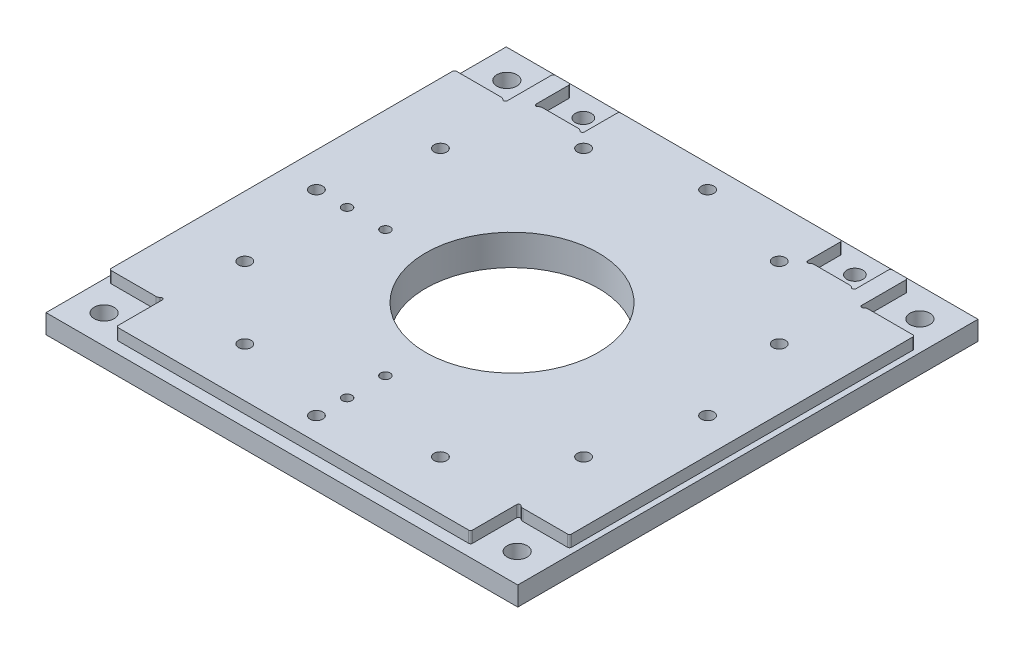
SolidWorks part; units mm, degrees
ref_plane "Front Plane" through (0, 0, 0) normal (0, 0, 1) x (1, 0, 0)
ref_plane "Top Plane" through (0, 0, 0) normal (0, 1, 0) x (1, 0, 0)
ref_plane "Right Plane" through (0, 0, 0) normal (1, 0, 0) x (0, 0, -1)
other "Configuration Table"
sketch "草图1" plane through (0, 0, 0) normal (0, 1, 0) x (1, 0, 0)
  line L1 (-60, 60) -> (60, 60)
  line L2 (-60, 60) -> (-60, -60)
  line L3 (-60, -60) -> (60, -60)
  line L4 (60, 60) -> (60, -60)
  line L5 (-60, 60) -> (60, -60) construction
  line L6 (-60, -60) -> (60, 60) construction
  point P0 (0, 0)
extrude "凸台-拉伸1" add sketch "草图1" along normal blind 3
sketch "草图3" plane through (0, 0, 0) normal (0, -1, 0) x (1, 0, 0)
  line L0 (-60, 60) -> (60, 60) construction
  line L6 (-61.5, 60) -> (61.5, 60)
  line L7 (-61.5, 60) -> (-61.5, -60)
  line L8 (-61.5, -60) -> (61.5, -60)
  line L9 (61.5, 60) -> (61.5, -60)
  line L10 (-61.5, 60) -> (61.5, -60) construction
  line L11 (-61.5, -60) -> (61.5, 60) construction
  line L12 (60, 60) -> (60, -60) construction
  point P0 (0, 0)
  dimension "D1" = 0
  dimension "D2" = 1.5
extrude "凸台-拉伸2" add sketch "草图3" along normal blind 5
sketch "草图2" plane through (0, 3, 0) normal (0, 1, 0) x (1, 0, 0)
  line L0 (0, 0) -> (0, 51) construction
  circle A0 centre (0, 51) radius 1.65
  circle A1 centre (25.5, 44.1673) radius 1.65
  circle A2 centre (44.1673, 25.5) radius 1.65
  circle A3 centre (51, 0) radius 1.65
  circle A4 centre (44.1673, -25.5) radius 1.65
  circle A5 centre (25.5, -44.1673) radius 1.65
  circle A6 centre (0, -51) radius 1.65
  circle A7 centre (-25.5, -44.1673) radius 1.65
  circle A8 centre (-44.1673, -25.5) radius 1.65
  circle A9 centre (-51, 0) radius 1.65
  circle A10 centre (-44.1673, 25.5) radius 1.65
  circle A11 centre (-25.5, 44.1673) radius 1.65
  point P29 (0, 0)
  dimension "D1" = 12
extrude "切除-拉伸1" cut sketch "草图2" against normal through all contours A9 | A8 | A7 | A6 | A5 | A4 | A11 | A10 | A0 | A1 | A2 | A3
sketch "草图5" plane through (0, 3, 0) normal (0, 1, 0) x (1, 0, 0)
  line L0 (-61.5, 60) -> (-46.2, 60)
  line L1 (60, 60) -> (-60, 60) construction
  line L2 (-46.2, 60) -> (-46.2, 45)
  line L3 (-46.2, 45) -> (-61.5, 45)
  line L4 (-61.5, -60) -> (-61.5, 60) construction
  line L5 (-61.5, 45) -> (-61.5, 60)
  line L6 (46.2, 60) -> (46.2, 45)
  line L7 (46.2, 45) -> (61.5, 45)
  line L8 (61.5, 60) -> (61.5, -60) construction
  line L9 (61.5, 45) -> (61.5, 60)
  line L10 (61.5, 60) -> (46.2, 60)
  line L11 (-41.7, 60) -> (-41.7, 48)
  line L12 (-41.7, 48) -> (-29.1, 48)
  line L13 (-29.1, 48) -> (-29.1, 60)
  line L14 (-29.1, 60) -> (-41.7, 60)
  line L15 (41.7, 60) -> (41.7, 48)
  line L16 (41.7, 48) -> (29.1, 48)
  line L17 (29.1, 48) -> (29.1, 60)
  line L18 (29.1, 60) -> (41.7, 60)
  line L19 (-61.5, -60) -> (-46.2, -60)
  line L20 (-46.2, -60) -> (-46.2, -45)
  line L21 (-46.2, -45) -> (-61.5, -45)
  line L22 (-61.5, -45) -> (-61.5, -60)
  line L23 (61.5, -60) -> (46.2, -60)
  line L24 (-60, -60) -> (60, -60) construction
  line L25 (46.2, -60) -> (46.2, -45)
  line L26 (46.2, -45) -> (61.5, -45)
  line L27 (61.5, -45) -> (61.5, -60)
  dimension "D1" = 4.5
  dimension "D2" = 4.5
extrude "切除-拉伸2" cut sketch "草图5" against normal blind 3
sketch "草图6" plane through (0, 3, 0) normal (0, 1, 0) x (1, 0, 0)
  line L0 (41.7, 60) -> (41.7, 48) construction
  line L1 (-61.5, -60) -> (-61.5, 60) construction
  line L2 (41.7, 54) -> (29.1, 54) construction
  line L3 (61.5, 60) -> (61.5, -60) construction
  line L4 (-46.2, 60) -> (-46.2, 45) construction
  line L5 (-46.2, 52.5) -> (-61.5, 52.5) construction
  line L6 (-29.1, 60) -> (-29.1, 48) construction
  line L7 (29.1, 60) -> (29.1, 48) construction
  line L8 (46.2, -52.5) -> (61.5, -52.5) construction
  line L9 (-46.2, -52.5) -> (-61.5, -52.5) construction
  line L10 (-29.1, 54) -> (-41.7, 54) construction
  line L15 (-41.7, 60) -> (-41.7, 48) construction
  line L17 (46.2, 60) -> (46.2, 45) construction
  line L18 (46.2, 52.5) -> (61.5, 52.5) construction
  line L19 (-46.2, -60) -> (-46.2, -45) construction
  line L20 (46.2, -45) -> (46.2, -60) construction
  circle A4 centre (-53.85, -52.5) radius 2.6
  circle A5 centre (53.85, -52.5) radius 2.6
  circle A6 centre (-53.85, 52.5) radius 2.6
  circle A7 centre (-35.4, 54) radius 2.1
  circle A9 centre (53.85, 52.5) radius 2.6
  circle A10 centre (35.4, 54) radius 2.1
extrude "切除-拉伸3" cut sketch "草图6" against normal through all
sketch "草图7" plane through (0, -5, 0) normal (0, -1, 0) x (1, 0, 0)
  circle A0 centre (-53.85, 52.5) radius 5.5
  circle A1 centre (-53.85, -52.5) radius 5.5
  circle A2 centre (-35.4, -54) radius 4.6
  circle A3 centre (53.85, 52.5) radius 5.5
  circle A4 centre (53.85, -52.5) radius 5.5
  circle A5 centre (35.4, -54) radius 4.6
extrude "切除-拉伸4" cut sketch "草图7" against normal blind 1
sketch "草图8" plane through (0, 3, 0) normal (0, 1, 0) x (1, 0, 0)
  circle A0 centre (0, 0) radius 22.5
  dimension "D1" = 45
extrude "切除-拉伸5" cut sketch "草图8" against normal through all
sketch "草图9" plane through (0, 3, 0) normal (0, 1, 0) x (1, 0, 0)
  line L0 (0, 0) -> (0, -60) construction
  line L1 (-46.2, -60) -> (46.2, -60) construction
  line L2 (0, -43) -> (0, -33)
  line L3 (-43, 0) -> (-33, 0)
  circle A0 centre (0, -43) radius 1.25
  circle A1 centre (0, -33) radius 1.25
  circle A2 centre (-43, 0) radius 1.25
  circle A3 centre (-33, 0) radius 1.25
  point P16 (0, 0)
  dimension "D1" = 2
extrude "切除-拉伸6" cut sketch "草图9" against normal through all
sketch "草图11" plane through (0, 3, 0) normal (0, 1, 0) x (1, 0, 0)
  line L0 (-46.2, -60) -> (-46.2, -57)
  line L1 (-46.2, -60) -> (-46.2, -45) construction
  line L2 (-46.2, -57) -> (46.2, -57)
  line L3 (46.2, -45) -> (46.2, -60) construction
  line L4 (46.2, -57) -> (46.2, -60)
  line L5 (-46.2, -60) -> (46.2, -60) construction
  line L6 (46.2, -60) -> (-46.2, -60)
  line L7 (46.2, 60) -> (46.2, 57)
  line L8 (46.2, 60) -> (46.2, 45) construction
  line L9 (46.2, 57) -> (-46.2, 57)
  line L10 (-46.2, 45) -> (-46.2, 60) construction
  line L11 (-46.2, 57) -> (-46.2, 60)
  line L12 (-46.2, 60) -> (46.2, 60)
extrude "切除-拉伸7" cut sketch "草图11" against normal blind 3
fillet "圆角1" radius 0.5 12 edges at (-46.2, 1.5, -57) (-60, 1.5, -45) (-60, 1.5, 45) (-46.2, 1.5, 57) (46.2, 1.5, 57) (60, 1.5, 45) (60, 1.5, -45) (46.2, 1.5, -57) (41.7, 1.5, -57) (29.1, 1.5, -57) (-29.1, 1.5, -57) (-41.7, 1.5, -57)
sketch "草图12" plane through (0, 3, 0) normal (0, 1, 0) x (1, 0, 0)
  line L0 (-46.2, 45) -> (-46.7, 45) construction
  line L1 (-41.7, 48) -> (-41.2, 48) construction
  line L2 (-41.7, 48) -> (-29.1, 48) construction
  line L3 (-46.2, -45) -> (-46.7, -45) construction
  line L4 (29.1, 48) -> (41.7, 48) construction
  line L5 (41.2, 48) -> (41.7, 48) construction
  line L6 (46.2, 45) -> (46.7, 45) construction
  line L7 (46.2, -45) -> (46.7, -45) construction
  line L8 (-59.5, 45) -> (-46.2, 45) construction
  line L9 (29.1, 48) -> (41.7, 48) construction
  line L10 (-41.7, 48) -> (-29.1, 48) construction
  line L11 (29.1, 48) -> (41.7, 48) construction
  line L12 (-46.2, -45) -> (-59.5, -45) construction
  line L13 (59.5, -45) -> (46.2, -45) construction
  line L14 (-29.1, 48) -> (-29.6, 48) construction
  line L15 (46.2, 45) -> (59.5, 45) construction
  line L16 (-41.7, 48) -> (-29.1, 48) construction
  line L17 (29.1, 48) -> (29.6, 48) construction
  circle A3 centre (-46.7, 45) radius 0.5
  circle A4 centre (-41.2, 48) radius 0.5
  circle A6 centre (-46.7, -45) radius 0.5
  circle A8 centre (41.2, 48) radius 0.5
  circle A11 centre (46.7, -45) radius 0.5
  circle A12 centre (46.7, 45) radius 0.5
  circle A13 centre (-29.6, 48) radius 0.5
  circle A14 centre (29.6, 48) radius 0.5
extrude "切除-拉伸8" cut sketch "草图12" against normal up to surface (3 mm away)
fillet "圆角2" radius 1 8 edges at (-47.2, 1.5, 45) (-40.7, 1.5, -48) (-47.2, 1.5, -45) (40.7, 1.5, -48) (47.2, 1.5, -45) (47.2, 1.5, 45) (-30.1, 1.5, -48) (30.1, 1.5, -48)
sketch "草图13" plane through (0, -5, 0) normal (0, -1, 0) x (1, 0, 0)
  circle A0 centre (0, 0) radius 57.5
split line "分割线2"
